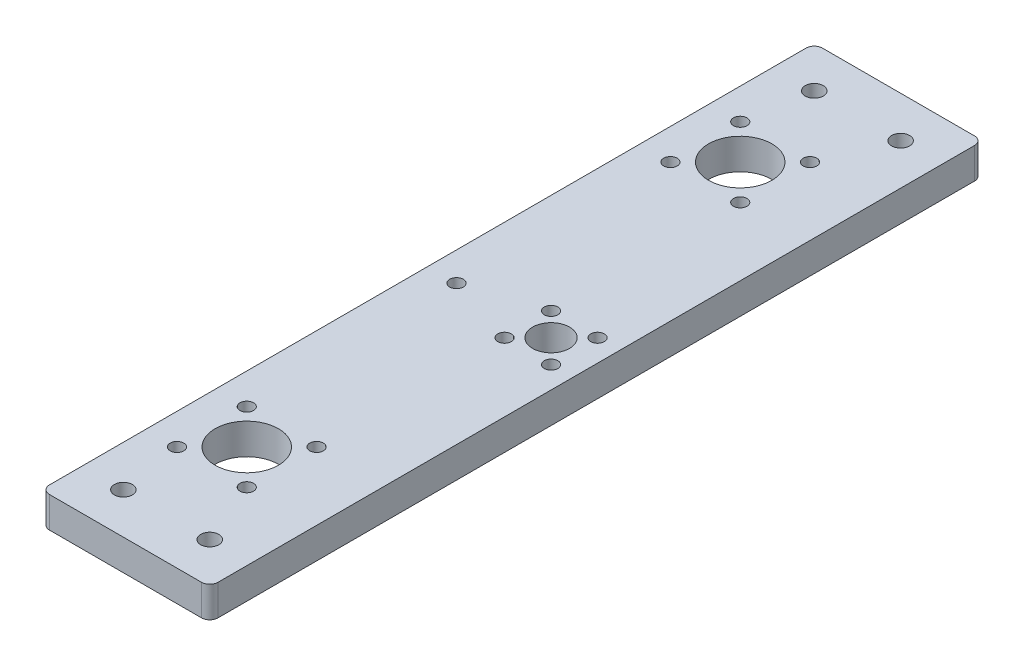
SolidWorks part; units mm, degrees
ref_plane "前视基准面" through (0, 0, 0) normal (0, 0, 1) x (1, 0, 0)
ref_plane "上视基准面" through (0, 0, 0) normal (0, 1, 0) x (1, 0, 0)
ref_plane "右视基准面" through (0, 0, 0) normal (1, 0, 0) x (0, 0, -1)
ref_plane "基准面1" through (0, 7.5, 0) normal (0, 1, 0) x (1, 0, 0)
sketch "草图1" plane through (0, 7.5, 0) normal (0, 1, 0) x (1, 0, 0)
  line L0 (18.5, 94) -> (-18.5, 94)
  line L1 (-20.5, 92) -> (-20.5, -92)
  line L2 (-18.5, -94) -> (18.5, -94)
  line L3 (20.5, -92) -> (20.5, 92)
  circle A0 centre (10.5, 84) radius 2.2
  circle A1 centre (-10.5, 84) radius 2.2
  circle A2 centre (10.5, -84) radius 2.2
  circle A3 centre (-10.5, -84) radius 2.2
  circle A4 centre (3.9853, 51.5147) radius 1.65
  circle A5 centre (15.1569, 5.6569) radius 1.65
  circle A6 centre (-12.9853, -68.4853) radius 1.65
  circle A7 centre (3.9853, -68.4853) radius 1.65
  circle A8 centre (-4.5, -60) radius 7.7
  circle A9 centre (9.5, 0) radius 4.5
  circle A10 centre (-12.9853, -51.5147) radius 1.65
  circle A11 centre (3.9853, -51.5147) radius 1.65
  circle A12 centre (3.9853, 68.4853) radius 1.65
  circle A13 centre (-12.9853, 68.4853) radius 1.65
  circle A14 centre (-12.9853, 51.5147) radius 1.65
  circle A15 centre (3.8431, 5.6569) radius 1.65
  circle A16 centre (3.8431, -5.6569) radius 1.65
  circle A17 centre (15.1569, -5.6569) radius 1.65
  circle A18 centre (-13.5, 0) radius 1.65
  circle A19 centre (-4.5, 60) radius 7.7
  arc A20 (-18.5, 94) -> (-20.5, 92) centre (-18.5, 92) ccw
  arc A21 (-20.5, -92) -> (-18.5, -94) centre (-18.5, -92) ccw
  arc A22 (18.5, -94) -> (20.5, -92) centre (18.5, -92) ccw
  arc A23 (20.5, 92) -> (18.5, 94) centre (18.5, 92) ccw
extrude "凸台-拉伸1" add sketch "草图1" against normal blind 7.5
